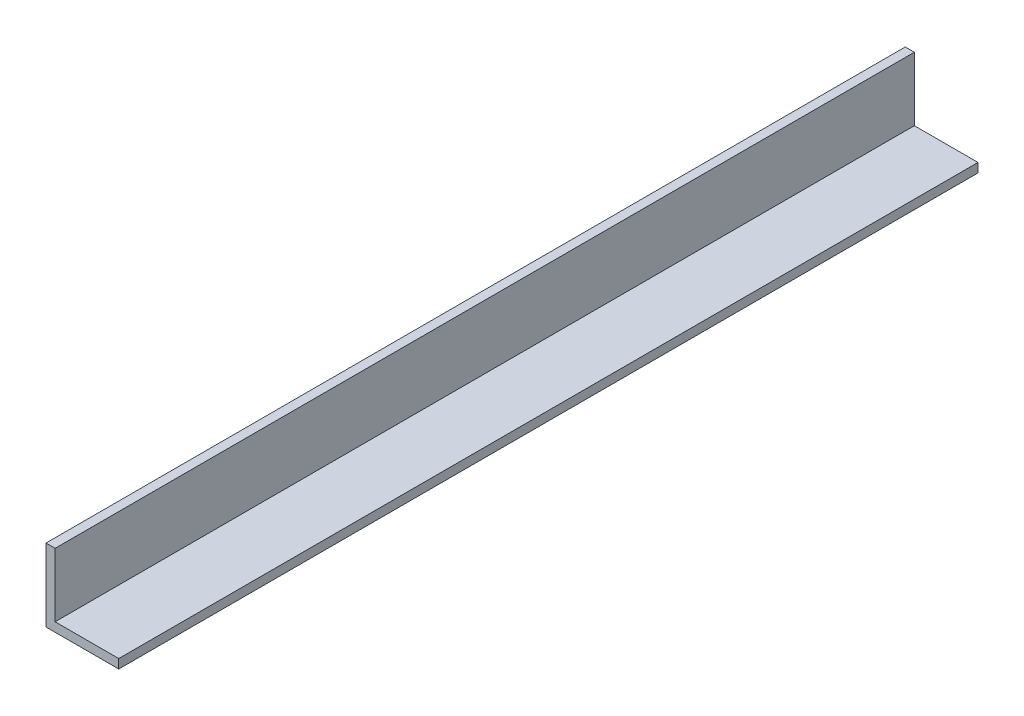
SolidWorks part; units mm, degrees
ref_plane "Plano frontal" through (0, 0, 0) normal (0, 0, 1) x (1, 0, 0)
ref_plane "Plano superior" through (0, 0, 0) normal (0, 1, 0) x (1, 0, 0)
ref_plane "Plano direito" through (0, 0, 0) normal (1, 0, 0) x (0, 0, -1)
sketch "Esboço1" plane through (0, 0, 0) normal (0, 0, 1) x (1, 0, 0)
  line L0 (0, 0) -> (25.4, 0)
  line L1 (25.4, 0) -> (25.4, 3.18)
  line L2 (25.4, 3.18) -> (3.18, 3.18)
  line L3 (3.18, 3.18) -> (3.18, 25.4)
  line L4 (3.18, 25.4) -> (0, 25.4)
  line L5 (0, 25.4) -> (0, 0)
  dimension "D1" = 3.18
  dimension "D2" = 3.18
  dimension "D3" = 25.4
  dimension "D4" = 25.4
extrude "Ressalto-extrusão1" add sketch "Esboço1" along normal blind 300
